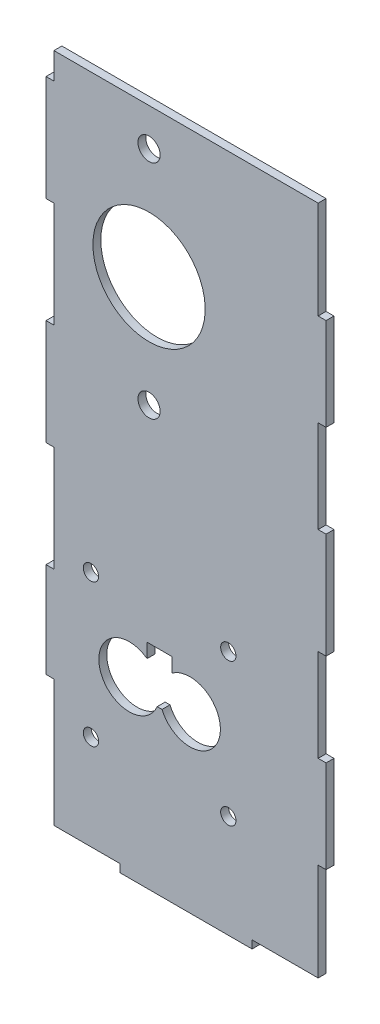
SolidWorks part; units mm, degrees
ref_plane "Front Plane" through (0, 0, 0) normal (0, 0, 1) x (1, 0, 0)
ref_plane "Top Plane" through (0, 0, 0) normal (0, 1, 0) x (1, 0, 0)
ref_plane "Right Plane" through (0, 0, 0) normal (1, 0, 0) x (0, 0, -1)
sketch "Sketch1" plane through (0, 0, 0) normal (0, 0, 1) x (1, 0, 0)
  line L1 (-50, 127) -> (50, 127)
  line L2 (-50, 127) -> (-50, -127)
  line L3 (-50, -127) -> (50, -127)
  line L4 (50, 127) -> (50, -127)
  dimension "D1" = 254
  dimension "D2" = 100
  dimension "D3" = 50
  dimension "D4" = 127
extrude "Boss-Extrude1" add sketch "Sketch1" along normal blind 3
sketch "Sketch2" plane through (0, -127, 0) normal (0, -1, 0) x (1, 0, 0)
  line L0 (-50, 0) -> (50, 0) construction
  line L1 (25, 0) -> (-25, 0)
  line L2 (25, 0) -> (25, 3)
  line L3 (25, 3) -> (-25, 3)
  line L4 (-25, 0) -> (-25, 3)
  line L5 (25, 0) -> (25, 3) construction
  line L6 (-50, 3) -> (50, 3) construction
  line L7 (-25, 3) -> (-25, 0) construction
extrude "Boss-Extrude2" add sketch "Sketch2" along normal blind 3
sketch "Sketch3" plane through (50, 0, 0) normal (1, 0, 0) x (0, 0, -1)
  line L0 (-3, -127) -> (-3, 127) construction
  line L1 (-3, 55) -> (0, 55)
  line L2 (-3, 55) -> (-3, 90)
  line L3 (-3, 90) -> (0, 90)
  line L4 (0, 55) -> (0, 90)
  line L5 (-3, 55) -> (0, 55) construction
  line L6 (0, -127) -> (0, 127) construction
  line L7 (-3, 90) -> (0, 90) construction
  line L8 (-3, -20) -> (0, -20) construction
  line L9 (-3, -20) -> (0, -20)
  line L10 (-3, -20) -> (-3, 20)
  line L11 (-3, 20) -> (0, 20)
  line L12 (0, -20) -> (0, 20)
  line L13 (-3, 20) -> (0, 20) construction
  line L14 (-3, -90) -> (0, -90) construction
  line L15 (-3, -90) -> (0, -90)
  line L16 (-3, -90) -> (-3, -55)
  line L17 (-3, -55) -> (0, -55)
  line L18 (0, -90) -> (0, -55)
  line L19 (-3, -55) -> (0, -55) construction
extrude "Boss-Extrude3" add sketch "Sketch3" along normal blind 3
sketch "Sketch4" plane through (0, 0, 0) normal (0, 0, -1) x (-1, 0, 0)
  line L0 (-50, 127) -> (50, 127) construction
  line L1 (50, 127) -> (50, -127) construction
  line L11 (25, -130) -> (-25, -130) construction
  line L12 (-22, -31) -> (42, -31) construction
  line L13 (-22, -31) -> (-22, -97) construction
  line L14 (-22, -97) -> (42, -97) construction
  line L15 (42, -31) -> (42, -97) construction
  line L16 (9.083, -68.5) -> (10.917, -68.5)
  line L18 (10, -49.3) -> (14.75, -49.3)
  line L19 (14.75, -49.3) -> (14.75, -54.6894)
  line L20 (10, -49.3) -> (5.25, -49.3)
  line L21 (5.25, -49.3) -> (5.25, -54.6894)
  circle A0 centre (14, 112.8) radius 4.2
  circle A1 centre (14, 70.8) radius 21.25
  circle A2 centre (14, 28.8) radius 4.2
  circle A9 centre (-16, -37) radius 2.9
  circle A10 centre (36, -37) radius 2.9
  circle A11 centre (36, -91) radius 2.9
  circle A12 centre (-16, -91) radius 2.9
  arc A13 (5.25, -54.6894) -> (9.083, -68.5) centre (-1.5, -64) ccw
  arc A14 (10.917, -68.5) -> (14.75, -54.6894) centre (21.5, -64) ccw
  dimension "D1" = 42
  dimension "D2" = 42
  dimension "D3" = 8.4
  dimension "D4" = 8.4
  dimension "D5" = 10
  dimension "D6" = 42.5
  dimension "D7" = 36
  dimension "D8" = 66
  dimension "D9" = 64
  dimension "D17" = 23
  dimension "D18" = 23
  dimension "D19" = 4.5
  dimension "D20" = 4.75
  dimension "D12" = 5.8
  dimension "D13" = 6
  dimension "D14" = 6
  dimension "D10" = 8
  dimension "D11" = 33
  dimension "D15" = 2
  dimension "D16" = 2
  dimension "D21" = 4.75
  dimension "D22" = 14.7
  dimension "D23" = 33
  dimension "D24" = 20.5
  dimension "D25" = 6.75
  dimension "D26" = 6.75
extrude "Cut-Extrude1" cut sketch "Sketch4" against normal blind 3
sketch "Sketch5" plane through (-50, 0, 0) normal (-1, 0, 0) x (0, 0, 1)
  line L0 (0, 127) -> (0, -127) construction
  line L1 (0, -43) -> (3, -43)
  line L2 (0, -43) -> (0, -79)
  line L3 (0, -79) -> (3, -79)
  line L4 (3, -43) -> (3, -79)
  line L5 (3, -43) -> (0, -43) construction
  line L6 (3, 127) -> (3, -127) construction
  line L7 (0, -79) -> (3, -79) construction
  line L8 (3, 37) -> (0, 37) construction
  line L9 (0, 37) -> (3, 37)
  line L10 (0, 37) -> (0, -3)
  line L11 (0, -3) -> (3, -3)
  line L12 (3, 37) -> (3, -3)
  line L13 (0, -3) -> (3, -3) construction
  line L14 (0, 77) -> (3, 77) construction
  line L15 (0, 77) -> (3, 77)
  line L16 (0, 77) -> (0, 117)
  line L17 (0, 117) -> (3, 117)
  line L18 (3, 77) -> (3, 117)
  line L19 (3, 117) -> (0, 117) construction
extrude "Boss-Extrude4" add sketch "Sketch5" along normal blind 3
